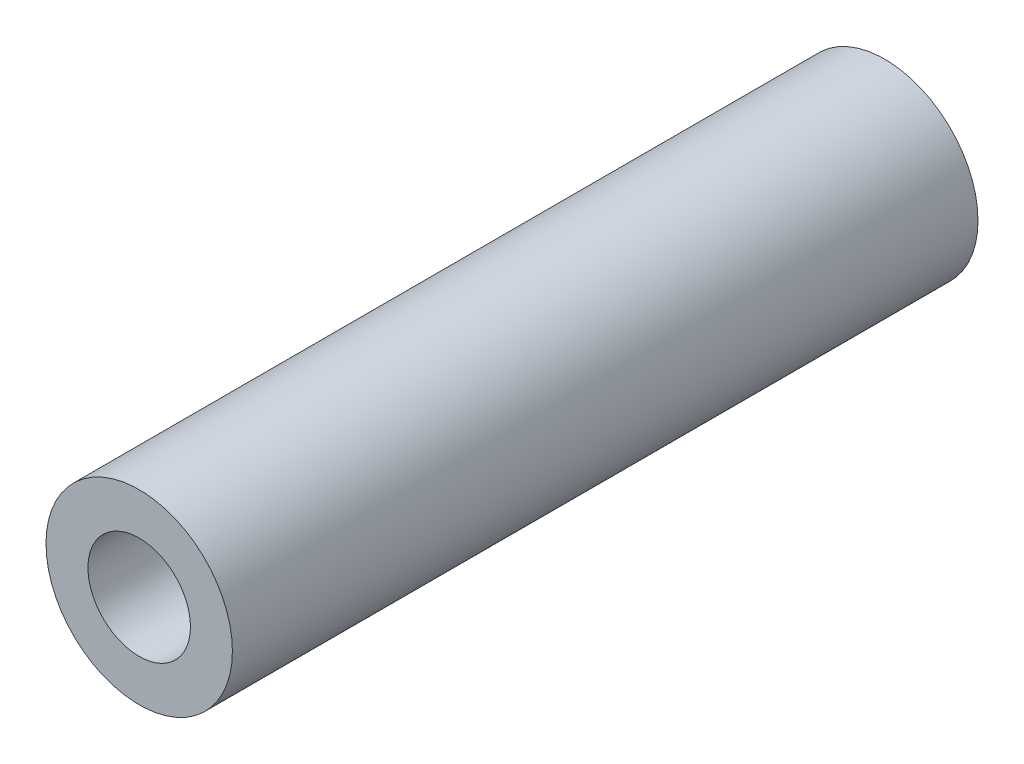
SolidWorks part; units mm, degrees
ref_plane "Front Plane" through (0, 0, 0) normal (0, 0, 1) x (1, 0, 0)
ref_plane "Top Plane" through (0, 0, 0) normal (0, 1, 0) x (1, 0, 0)
ref_plane "Right Plane" through (0, 0, 0) normal (1, 0, 0) x (0, 0, -1)
sketch "Sketch1" plane through (0, 0, 0) normal (0, 0, 1) x (1, 0, 0)
  circle A0 centre (0, 0) radius 1.65
  circle A1 centre (0, 0) radius 3
  dimension "D1" = 3.3
  dimension "D2" = 6
extrude "Boss-Extrude1" add sketch "Sketch1" along normal mid plane 24
